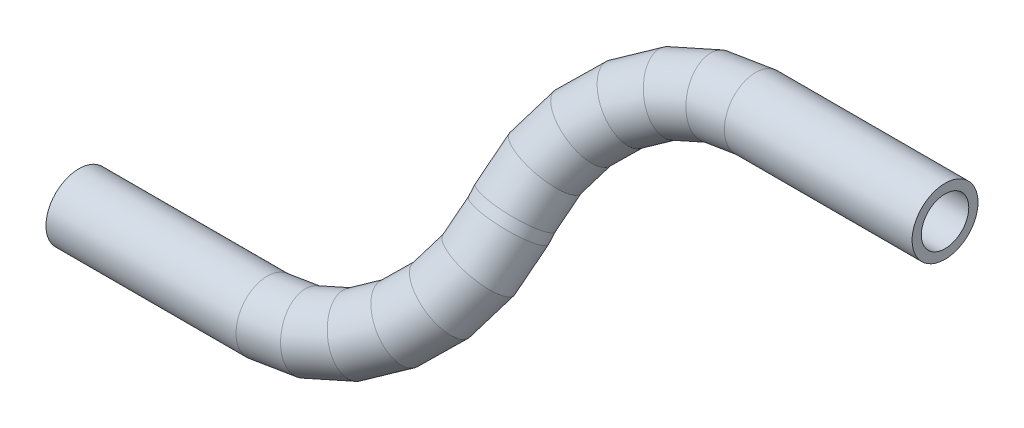
SolidWorks part; units mm, degrees
ref_plane "Front Plane" through (0, 0, 0) normal (0, 0, 1) x (1, 0, 0)
ref_plane "Top Plane" through (0, 0, 0) normal (0, 1, 0) x (1, 0, 0)
ref_plane "Right Plane" through (0, 0, 0) normal (1, 0, 0) x (0, 0, -1)
sketch3d "Path"
  line L0 (-2754.8928, -26.6976, 19.3969) -> (-2773.0928, -26.6976, 19.3969)
  line L1 (-2773.0928, -26.6976, 19.3969) -> (-2776.8139, -27.0769, 19.6725)
  line L2 (-2776.8139, -27.0769, 19.6725) -> (-2780.3024, -28.1912, 20.4821)
  line L3 (-2780.3024, -28.1912, 20.4821) -> (-2783.3401, -29.9708, 21.7751)
  line L4 (-2783.3401, -29.9708, 21.7751) -> (-2785.7372, -32.3044, 23.4705)
  line L5 (-2785.7372, -32.3044, 23.4705) -> (-2787.3438, -35.0462, 25.4625)
  line L6 (-2787.3438, -35.0462, 25.4625) -> (-2788.0595, -38.0247, 27.6266)
  line L7 (-2788.0595, -38.0247, 27.6266) -> (-2788.1261, -38.8319, 28.213)
  line L8 (-2788.1261, -38.8319, 28.213) -> (-2788.8417, -41.8104, 30.3771)
  line L9 (-2788.8417, -41.8104, 30.3771) -> (-2790.4483, -44.5522, 32.3691)
  line L10 (-2790.4483, -44.5522, 32.3691) -> (-2792.8454, -46.8858, 34.0645)
  line L11 (-2792.8454, -46.8858, 34.0645) -> (-2795.8832, -48.6654, 35.3575)
  line L12 (-2795.8832, -48.6654, 35.3575) -> (-2799.3717, -49.7797, 36.1671)
  line L13 (-2799.3717, -49.7797, 36.1671) -> (-2803.0928, -50.1591, 36.4427)
  line L14 (-2803.0928, -50.1591, 36.4427) -> (-2821.2928, -50.1591, 36.4427)
ref_plane "Start Plane" through (-2754.8928, 0, 0) normal (1, 0, 0) x (0, 0, -1)
sketch "Profile" plane through (-2754.8928, 0, 0) normal (1, 0, 0) x (0, 0, -1)
  circle A0 centre (-19.3969, -26.6976) radius 3.175
  circle A1 centre (-19.3969, -26.6976) radius 2.286
sweep "Tube" add profiles "Profile" path "Path"
